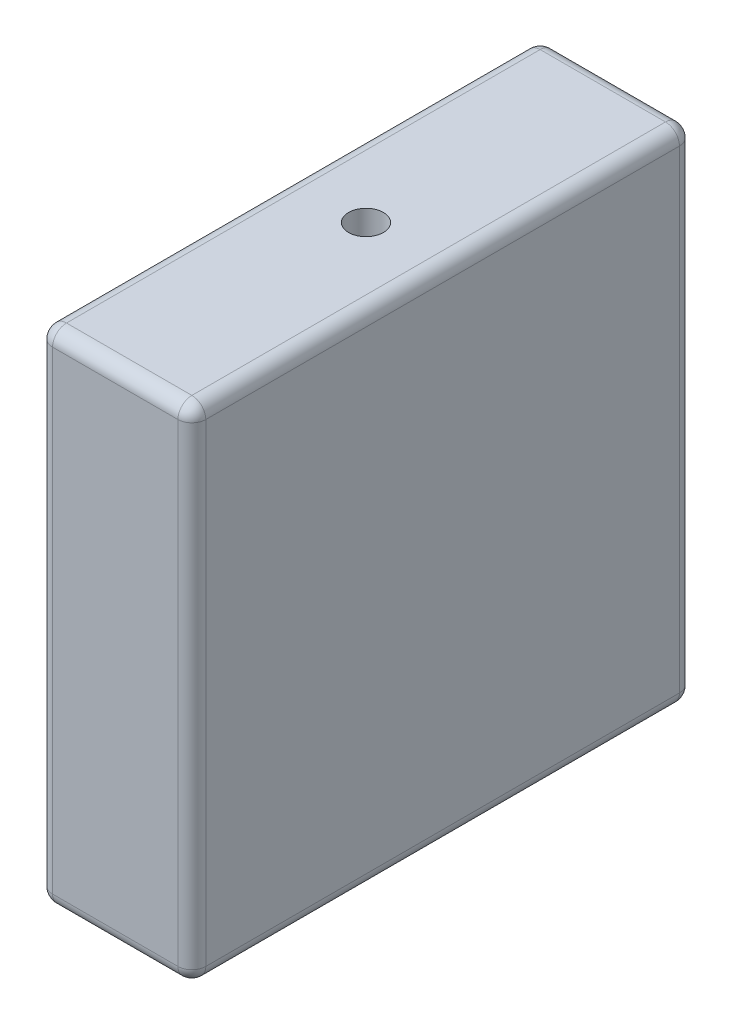
SolidWorks part; units mm, degrees
ref_plane "前视基准面" through (0, 0, 0) normal (0, 0, 1) x (1, 0, 0)
ref_plane "上视基准面" through (0, 0, 0) normal (0, 1, 0) x (1, 0, 0)
ref_plane "右视基准面" through (0, 0, 0) normal (1, 0, 0) x (0, 0, -1)
sketch "草图1" plane through (0, 0, 0) normal (1, 0, 0) x (0, 0, -1)
  line L1 (-30.7353, 27.3964) -> (5.2647, 27.3964)
  line L2 (-30.7353, 27.3964) -> (-30.7353, -8.6036)
  line L3 (-30.7353, -8.6036) -> (5.2647, -8.6036)
  line L4 (5.2647, 27.3964) -> (5.2647, -8.6036)
  dimension "D1" = 36
extrude "凸台-拉伸1" add sketch "草图1" along normal blind 11
fillet "圆角1" radius 1 12 edges at (5.5, -8.6036, -5.2647) (5.5, 27.3964, -5.2647) (0, -8.6036, 12.7353) (0, 9.3964, -5.2647) (0, 27.3964, 12.7353) (5.5, 27.3964, 30.7353) (5.5, -8.6036, 30.7353) (0, 9.3964, 30.7353) (11, 27.3964, 12.7353) (11, 9.3964, -5.2647) (11, -8.6036, 12.7353) (11, 9.3964, 30.7353)
sketch "草图2" plane through (0, -8.6036, 0) normal (0, -1, 0) x (1, 0, 0)
  line L0 (11, 29.7353) -> (11, -4.2647) construction
  line L1 (1, -4.2647) -> (10, -4.2647) construction
  circle A0 centre (5.5, 12.7353) radius 1.25
  point P4 (11, 12.7353)
  point P7 (5.5, -4.2647)
  dimension "D1" = 2.5
  dimension "D2" = 0
  dimension "D3" = 0
extrude "切除-拉伸1" cut sketch "草图2" against normal up to surface (36 mm away) up to face at (5.5, 27.3964, 12.7353)
